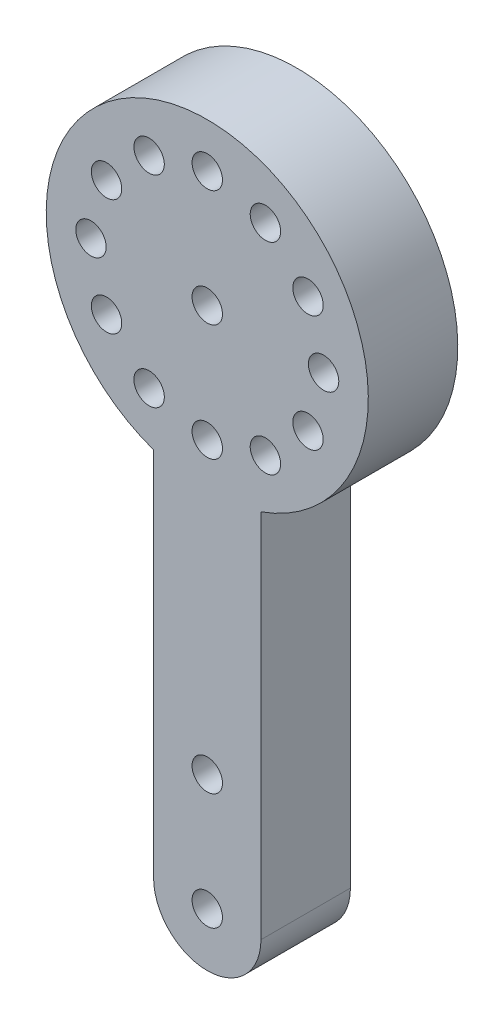
SolidWorks part; units mm, degrees
ref_plane "Front Plane" through (0, 0, 0) normal (0, 0, 1) x (1, 0, 0)
ref_plane "Top Plane" through (0, 0, 0) normal (0, 1, 0) x (1, 0, 0)
ref_plane "Right Plane" through (0, 0, 0) normal (1, 0, 0) x (0, 0, -1)
sketch "Sketch1" plane through (0, 0, 0) normal (0, 0, 1) x (1, 0, 0)
  line L0 (0, 0) -> (0, 40.5079) construction
  line L1 (0, 0) -> (0, 58.3878) construction
  line L2 (-6, 0) -> (-6, 41.4173)
  line L3 (6, 0) -> (6, 41.4173)
  line L4 (-6, 20.7086) -> (6, 20.7086) construction
  arc A0 (-6, 0) -> (6, 0) centre (0, 0) ccw
  circle A2 centre (0, 0) radius 1.7
  circle A3 centre (0, 13) radius 1.7
  arc A6 (6, 41.4173) -> (-6, 41.4173) centre (0, 58.3878) ccw
  circle A7 centre (0, 58.3878) radius 1.7
  circle A8 centre (0, 45.3878) radius 1.7
  circle A9 centre (-6.5, 47.1295) radius 1.7
  circle A10 centre (-11.2583, 51.8878) radius 1.7
  circle A11 centre (-13, 58.3878) radius 1.7
  circle A12 centre (-11.2583, 64.8878) radius 1.7
  circle A13 centre (-6.5, 69.6462) radius 1.7
  circle A14 centre (0, 71.3878) radius 1.7
  circle A15 centre (6.5, 69.6462) radius 1.7
  circle A16 centre (11.2583, 64.8878) radius 1.7
  circle A17 centre (13, 58.3878) radius 1.7
  circle A18 centre (11.2583, 51.8878) radius 1.7
  circle A19 centre (6.5, 47.1295) radius 1.7
  point P3 (0, 30)
  point P43 (0, 58.3878)
  dimension "D2" = 6
  dimension "D3" = 3.4
  dimension "D4" = 13
  dimension "D5" = 36
  dimension "D6" = 3.4
  dimension "D7" = 0
  dimension "D9" = 12
  dimension "D1" = 12
  dimension "D8" = 13
extrude "Boss-Extrude1" add sketch "Sketch1" along normal mid plane 10
